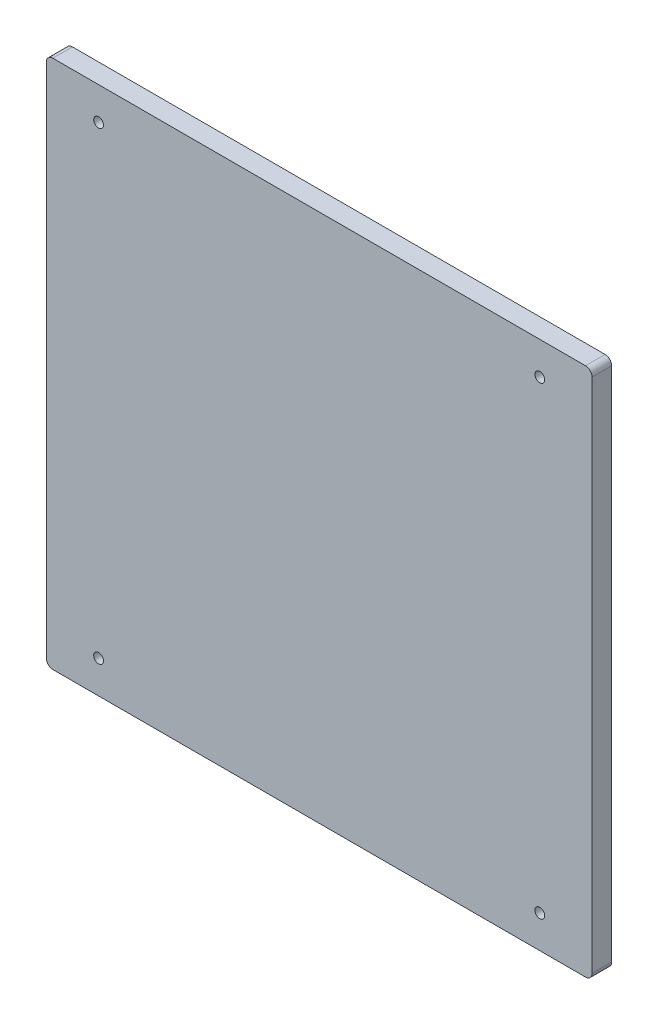
SolidWorks part; units mm, degrees
material "MDF"
ref_plane "Plano frontal" through (0, 0, 0) normal (0, 0, 1) x (1, 0, 0)
ref_plane "Plano superior" through (0, 0, 0) normal (0, 1, 0) x (1, 0, 0)
ref_plane "Plano direito" through (0, 0, 0) normal (1, 0, 0) x (0, 0, -1)
sketch "Esboço1" plane through (0, 0, 0) normal (0, 0, 1) x (1, 0, 0)
  line L0 (0, -25.1621) -> (0, 29.3505) construction
  line L1 (81.5, -81) -> (-81.5, -81)
  line L2 (83.5, -79) -> (83.5, 79)
  line L3 (81.5, 81) -> (-81.5, 81)
  line L4 (-83.5, -79) -> (-83.5, 79)
  circle A0 centre (-67.5, 71) radius 1.5
  circle A1 centre (67.5, 71) radius 1.5
  circle A2 centre (67.5, -71) radius 1.5
  circle A3 centre (-67.5, -71) radius 1.5
  arc A4 (81.5, -81) -> (83.5, -79) centre (81.5, -79) ccw
  arc A5 (-81.5, -81) -> (-83.5, -79) centre (-81.5, -79) cw
  arc A6 (83.5, 79) -> (81.5, 81) centre (81.5, 79) ccw
  arc A7 (-81.5, 81) -> (-83.5, 79) centre (-81.5, 79) ccw
  circle A8 centre (-62.6034, -71) radius 1.5 [skipped]
  circle A9 centre (62.6034, 71) radius 1.5 [skipped]
  point P0 (0, 0)
  dimension "D3" = 16
  dimension "D4" = 10
  dimension "D5" = 3
  dimension "D8" = 2
  dimension "D9" = 16
  dimension "D11" = 16
  dimension "D13" = 83.5
  dimension "D14" = 81
  dimension "D16" = 10
  dimension "D17" = 10
  dimension "D2" = 83.5
  dimension "D10" = 16
  dimension "D12" = 10
  dimension "D15" = 81
  dimension "D6" = 2
  dimension "D7" = 2
extrude "Ressalto-extrusão1" add sketch "Esboço1" along normal blind 6
sketch "Esboço2" plane through (0, 0, 0) normal (0, 0, -1) x (-1, 0, 0)
  line L1 (22.5, -60) -> (-22.5, -60) construction
  line L2 (22.5, -60) -> (22.5, 60) construction
  line L3 (22.5, 60) -> (-22.5, 60) construction
  line L4 (-22.5, -60) -> (-22.5, 60) construction
  line L5 (22.5, -60) -> (-22.5, 60) construction
  line L6 (22.5, 60) -> (-22.5, -60) construction
  point P0 (0, 0)
  dimension "D1" = 120
  dimension "D2" = 45
